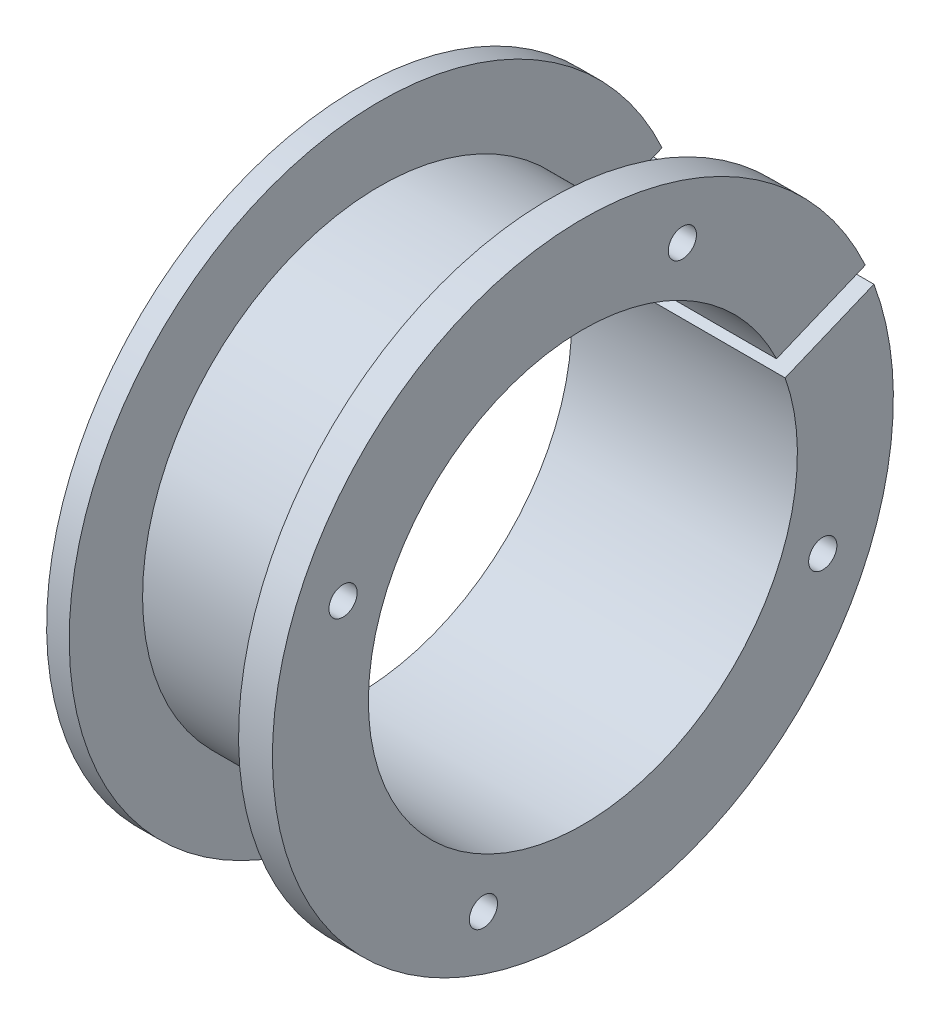
SolidWorks part; units mm, degrees
material "1060 Alloy"
ref_plane "Front Plane" through (0, 0, 0) normal (0, 0, 1) x (1, 0, 0)
ref_plane "Top Plane" through (0, 0, 0) normal (0, 1, 0) x (1, 0, 0)
ref_plane "Right Plane" through (0, 0, 0) normal (1, 0, 0) x (0, 0, -1)
sketch "Sketch1" plane through (0, 0, 0) normal (0, 0, 1) x (1, 0, 0)
  line L0 (0, 0) -> (-54.2563, 0) construction
  line L1 (0, 19) -> (-20, 19)
  line L2 (0, 19) -> (0, 27.5)
  line L3 (0, 27.5) -> (-3, 27.5)
  line L4 (-3, 27.5) -> (-3, 21)
  line L5 (-3, 21) -> (-18, 21)
  line L6 (-18, 21) -> (-18, 27.5)
  line L7 (-18, 27.5) -> (-20, 27.5)
  line L8 (-20, 27.5) -> (-20, 19)
  dimension "D1" = 19
  dimension "D2" = 27.5
  dimension "D3" = 2
  dimension "D4" = 2
  dimension "D5" = 3
  dimension "D6" = 15
revolve "Revolve1" add sketch "Sketch1" angle 360 about L0
hole_wizard "M3x0.5 Tapped Hole1" positions "Sketch3" profile "Sketch2" tap size "M3x0.5" standard "Ansi Metric"
sketch "Sketch3" plane through (0, 0, 0) normal (1, 0, 0) x (0, 0, -1)
  point P2 (-8.8101, -21.2457)
  point P5 (21.2457, -8.8101)
  point P8 (8.8101, 21.2457)
  point P11 (-21.2457, 8.8101)
sketch "Sketch2" plane through (0, -21.2457, 8.8101) normal (0, 1, 0) x (0, 0, -1)
  line L0 (0, 0) -> (0, 8.2511)
  line L1 (0, 8.2511) -> (1.25, 7.5)
  line L2 (1.25, 7.5) -> (1.25, 0)
  line L5 (1.25, 0) -> (0, 0)
  line L10 (0, 8.2511) -> (-1.25, 7.5) construction
  line L11 (0, -6.35) -> (0, 107.95) construction
  dimension "Tap Drill Dia." = 2.5
  dimension "Tap Drill Depth" = 7.5
  dimension "Drill Angle" = 118
cosmetic thread "Hole Thread1" parameters "D1"=4, "D2"=3
cosmetic thread "Hole Thread2" parameters "D1"=4, "D2"=3
cosmetic thread "Hole Thread3" parameters "D1"=4, "D2"=3
cosmetic thread "Hole Thread4" parameters "D1"=4, "D2"=3
sketch "Sketch4" plane through (-20, 0, 0) normal (-1, 0, 0) x (0, 0, 1)
  line L0 (0, 0) -> (-8.8101, 21.2457) construction
  line L1 (0, 0) -> (-21.2457, -8.8101) construction
  line L2 (-21.2457, -8.8101) -> (-8.8101, 21.2457) construction
  line L3 (0, 0) -> (-15.0279, 6.2178) construction
  line L4 (-25.7932, 9.5897) -> (-25.0285, 11.4378)
  line L5 (-25.0285, 11.4378) -> (-17.1499, 8.178)
  line L6 (-25.7932, 9.5897) -> (-17.9146, 6.3299)
  line L7 (-17.1499, 8.178) -> (-17.9146, 6.3299)
  circle A0 centre (-21.2457, -8.8101) radius 1.25 construction
  circle A1 centre (-8.8101, 21.2457) radius 1.25 construction
  circle A2 centre (0, 0) radius 27.5 construction
  circle A3 centre (0, 0) radius 19 construction
  dimension "D1" = 2
extrude "Cut-Extrude1" cut sketch "Sketch4" against normal through all
